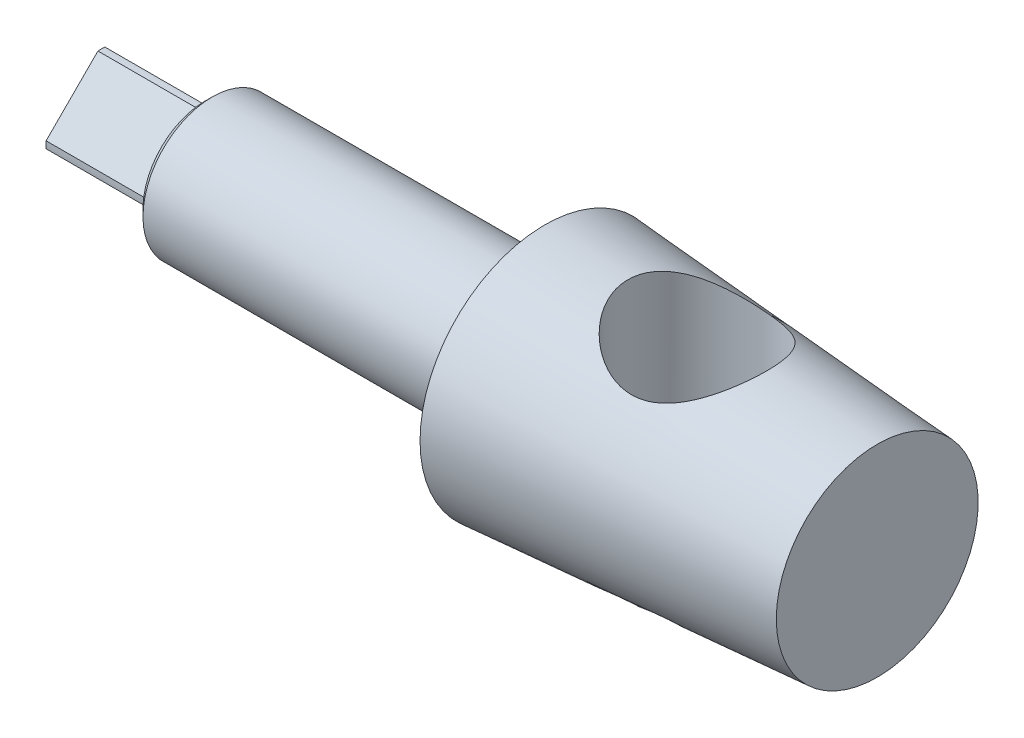
SolidWorks part; units mm, degrees
ref_plane "前视基准面" through (0, 0, 0) normal (0, 0, 1) x (1, 0, 0)
ref_plane "上视基准面" through (0, 0, 0) normal (0, 1, 0) x (1, 0, 0)
ref_plane "右视基准面" through (0, 0, 0) normal (1, 0, 0) x (0, 0, -1)
sketch "草图1" plane through (0, 0, 0) normal (0, 0, 1) x (1, 0, 0)
  line L0 (-69.9936, 0) -> (71.01, 0) construction
  line L1 (-64, 0) -> (-64, 8)
  line L2 (-64, 8) -> (-49, 8)
  line L3 (-49, 8) -> (-49, 10)
  line L4 (-49, 10) -> (0, 10)
  line L5 (0, 10) -> (0, 18)
  line L6 (0, 18) -> (48, 14.5714)
  line L7 (48, 14.5714) -> (48, 0)
  line L8 (48, 0) -> (-64, 0)
  dimension "D1" = 36
  dimension "D2" = 20
  dimension "D3" = 16
  dimension "D4" = 15
  dimension "D5" = 48
  dimension "D6" = 112
  dimension "D7" = 4.086
revolve "旋转1" add sketch "草图1" angle 360 about L0
sketch "草图2" plane through (0, 0, 0) normal (0, 1, 0) x (1, 0, 0)
  circle A0 centre (22, 0) radius 10
  dimension "D2" = 20
  dimension "D1" = 22
extrude "拉伸1" cut sketch "草图2" against normal through all and the other way through all
sketch "草图3" plane through (-64, 0, 0) normal (-1, 0, 0) x (0, 0, 1)
  line L0 (-8.4853, 0) -> (0, -8.4853)
  line L1 (-8.4853, 0) -> (0, 8.4853)
  line L2 (0, -8.4853) -> (8.4853, 0)
  line L3 (0, 8.4853) -> (8.4853, 0)
  line L4 (-8.4853, 0) -> (8.4853, 0) construction
  line L5 (0, -8.4853) -> (0, 8.4853) construction
  point P1 (0, 0)
  dimension "D1" = 12
extrude "拉伸2" cut sketch "草图3" against normal up to surface (15 mm away) flip side to cut up to face at (-49, 0, 8)
chamfer "倒角1" distance 1 angle 45 1 edges at (-49, 0, 10)
equation "\"D7@草图1\" =  atn( 1/14 ) "
